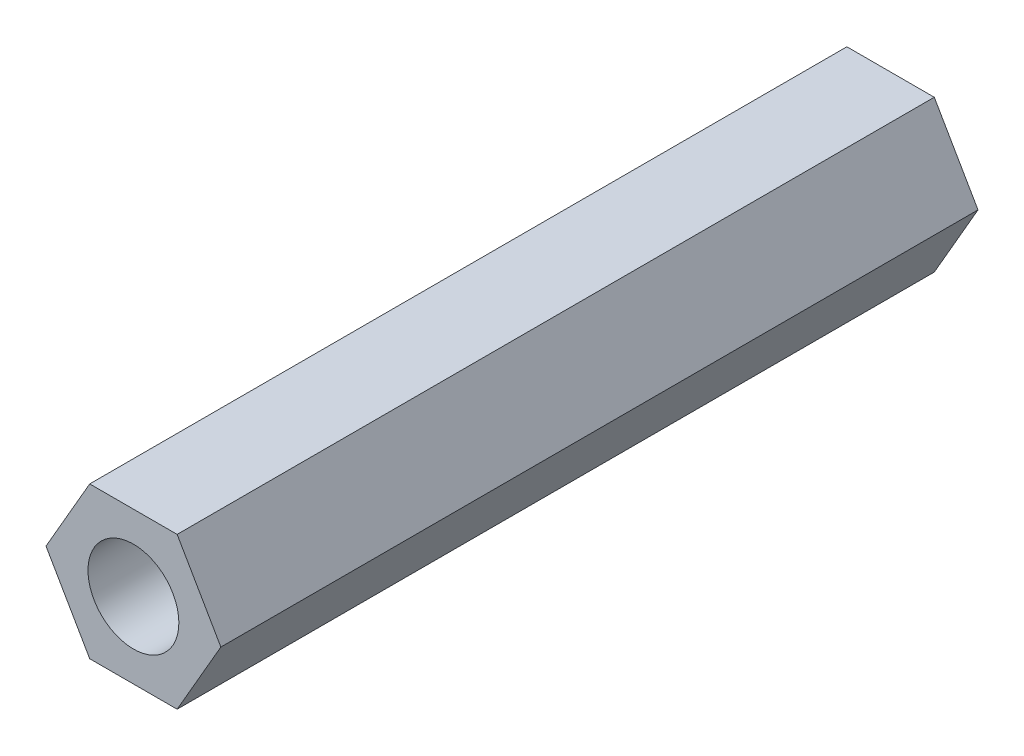
SolidWorks part; units mm, degrees
ref_plane "Ön Düzlem" through (0, 0, 0) normal (0, 0, 1) x (1, 0, 0)
ref_plane "Üst Düzlem" through (0, 0, 0) normal (0, 1, 0) x (1, 0, 0)
ref_plane "Sağ Düzlem" through (0, 0, 0) normal (1, 0, 0) x (0, 0, -1)
sketch "Çizim1" plane through (0, 0, 0) normal (0, 0, 1) x (1, 0, 0)
  line L1 (1.4434, -2.5) -> (2.8868, 0)
  line L2 (2.8868, 0) -> (1.4434, 2.5)
  line L3 (1.4434, 2.5) -> (-1.4434, 2.5)
  line L4 (-1.4434, 2.5) -> (-2.8868, 0)
  line L5 (-2.8868, 0) -> (-1.4434, -2.5)
  line L6 (-1.4434, -2.5) -> (1.4434, -2.5)
  circle A0 centre (0, 0) radius 2.5 construction
  circle A1 centre (0, 0) radius 1.5
  point P11 (0.5757, 0)
  dimension "D1" = 3
  dimension "D2" = 5
extrude "Yükseklik-Ekstrüzyon1" add sketch "Çizim1" along normal blind 25
